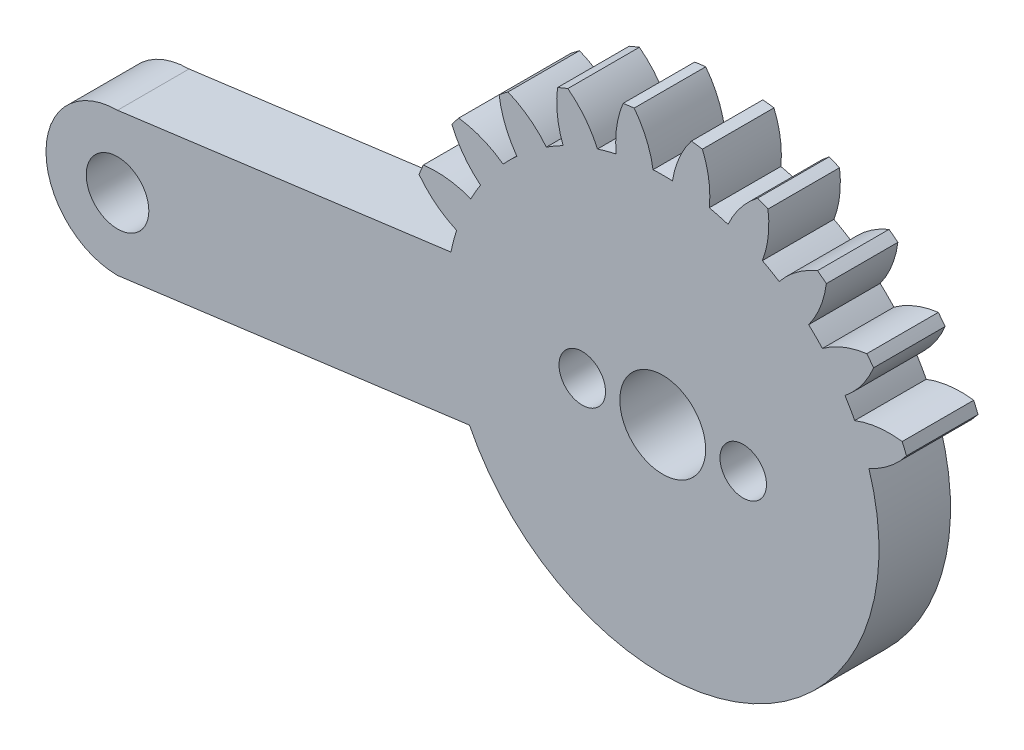
SolidWorks part; units mm, degrees
ref_plane "Front Plane" through (0, 0, 0) normal (0, 0, 1) x (1, 0, 0)
ref_plane "Top Plane" through (0, 0, 0) normal (0, 1, 0) x (1, 0, 0)
ref_plane "Right Plane" through (0, 0, 0) normal (1, 0, 0) x (0, 0, -1)
sketch "Sketch1" plane through (0, 0, 0) normal (0, 0, 1) x (1, 0, 0)
  line L0 (20.64, 4) -> (2.08, 4)
  line L1 (20.64, -4) -> (2.08, -4)
  circle A0 centre (-10.11, 0) radius 1.5
  circle A1 centre (20.64, 0) radius 1.5
  arc A2 (20.64, -4) -> (20.64, 4) centre (20.64, 0) ccw
  arc A3 (2.08, 4) -> (3.5201, 5.3071) centre (-0.7699, 8.5867) ccw
  arc A4 (3.5201, 5.3071) -> (3.2812, 5.8838) centre (-10.108, 0) ccw
  arc A5 (3.2812, 5.8838) -> (0.6255, 5.5703) centre (2.5667, 0.5313) ccw
  arc A6 (0.6255, 5.5703) -> (0.0827, 6.5103) centre (-10.108, 0) ccw
  arc A7 (0.0827, 6.5103) -> (1.6822, 8.6535) centre (-3.3105, 10.711) ccw
  arc A8 (1.6822, 8.6535) -> (1.3022, 9.1487) centre (-10.108, 0) ccw
  arc A9 (1.3022, 9.1487) -> (-1.182, 8.1585) centre (1.9973, 3.7936) ccw
  arc A10 (-1.182, 8.1585) -> (-1.9495, 8.926) centre (-10.108, 0) ccw
  arc A11 (-1.9495, 8.926) -> (-0.9593, 11.4102) centre (-6.3143, 12.1053) ccw
  arc A12 (-0.9593, 11.4102) -> (-1.4545, 11.7901) centre (-10.108, 0) ccw
  arc A13 (-1.4545, 11.7901) -> (-3.5977, 10.1907) centre (0.603, 6.7975) ccw
  arc A14 (-3.5977, 10.1907) -> (-4.5377, 10.7334) centre (-10.108, 0) ccw
  arc A15 (-4.5377, 10.7334) -> (-4.2242, 13.3892) centre (-9.5767, 12.6747) ccw
  arc A16 (-4.2242, 13.3892) -> (-4.8008, 13.6281) centre (-10.108, 0) ccw
  arc A17 (-4.8008, 13.6281) -> (-6.4571, 11.5285) centre (-1.5213, 9.3381) ccw
  arc A18 (-6.4571, 11.5285) -> (-7.5055, 11.8094) centre (-10.108, 0) ccw
  arc A19 (-7.5055, 11.8094) -> (-7.8901, 14.4558) centre (-12.8753, 12.3803) ccw
  arc A20 (-7.8901, 14.4558) -> (-8.5089, 14.5373) centre (-10.108, 0) ccw
  arc A21 (-8.5089, 14.5373) -> (-9.5653, 12.0806) centre (-4.2307, 11.2423) ccw
  arc A22 (-9.5653, 12.0806) -> (-10.6507, 12.0806) centre (-10.108, 0) ccw
  arc A23 (-10.6507, 12.0806) -> (-11.7071, 14.5373) centre (-15.9852, 11.2423) ccw
  arc A24 (-11.7071, 14.5373) -> (-12.3259, 14.4558) centre (-10.108, 0) ccw
  arc A25 (-12.3259, 14.4558) -> (-12.7104, 11.8094) centre (-7.3407, 12.3803) ccw
  arc A26 (-12.7104, 11.8094) -> (-13.7589, 11.5285) centre (-10.108, 0) ccw
  arc A27 (-13.7589, 11.5285) -> (-15.4151, 13.6281) centre (-18.6947, 9.3381) ccw
  arc A28 (-15.4151, 13.6281) -> (-15.9918, 13.3892) centre (-10.108, 0) ccw
  arc A29 (-15.9918, 13.3892) -> (-15.6783, 10.7334) centre (-10.6393, 12.6747) ccw
  arc A30 (-15.6783, 10.7334) -> (-16.6183, 10.1907) centre (-10.108, 0) ccw
  arc A31 (-16.6183, 10.1907) -> (-18.7615, 11.7901) centre (-20.819, 6.7975) ccw
  arc A32 (-18.7615, 11.7901) -> (-19.2567, 11.4102) centre (-10.108, 0) ccw
  arc A33 (-19.2567, 11.4102) -> (-18.2665, 8.926) centre (-13.9016, 12.1053) ccw
  arc A34 (-18.2665, 8.926) -> (-19.034, 8.1585) centre (-10.108, 0) ccw
  arc A35 (-19.034, 8.1585) -> (-21.5181, 9.1487) centre (-22.2133, 3.7936) ccw
  arc A36 (-21.5181, 9.1487) -> (-21.8981, 8.6535) centre (-10.108, 0) ccw
  arc A37 (-21.8981, 8.6535) -> (-20.2987, 6.5103) centre (-16.9054, 10.711) ccw
  arc A38 (-20.2987, 6.5103) -> (-20.8414, 5.5703) centre (-10.108, 0) ccw
  arc A39 (-20.8414, 5.5703) -> (-23.4972, 5.8838) centre (-22.7827, 0.5313) ccw
  arc A40 (-23.4972, 5.8838) -> (-23.7361, 5.3071) centre (-10.108, 0) ccw
  arc A41 (-23.7361, 5.3071) -> (-21.6364, 3.6509) centre (-19.446, 8.5867) ccw
  arc A42 (-21.6364, 3.6509) -> (-21.9174, 2.6025) centre (-10.108, 0) ccw
  arc A43 (-21.9174, 2.6025) -> (-24.5638, 2.2179) centre (-22.4883, -2.7673) ccw
  arc A44 (-24.5638, 2.2179) -> (-24.6453, 1.5991) centre (-10.108, 0) ccw
  arc A45 (-24.6453, 1.5991) -> (-22.1885, 0.5427) centre (-21.3503, 5.8773) ccw
  arc A46 (-22.1885, 0.5427) -> (-22.1885, -0.5427) centre (-10.108, 0) ccw
  arc A47 (-22.1885, -0.5427) -> (-24.6453, -1.5991) centre (-21.3503, -5.8773) ccw
  arc A48 (-24.6453, -1.5991) -> (-24.5638, -2.2179) centre (-10.108, 0) ccw
  arc A49 (-24.5638, -2.2179) -> (-21.9174, -2.6025) centre (-22.4883, 2.7673) ccw
  arc A50 (-21.9174, -2.6025) -> (-21.6364, -3.6509) centre (-10.108, 0) ccw
  arc A51 (-21.6364, -3.6509) -> (-23.7361, -5.3071) centre (-19.446, -8.5867) ccw
  arc A52 (-23.7361, -5.3071) -> (-23.4972, -5.8838) centre (-10.108, 0) ccw
  arc A53 (-23.4972, -5.8838) -> (-20.8414, -5.5703) centre (-22.7827, -0.5313) ccw
  arc A54 (-20.8414, -5.5703) -> (-20.2987, -6.5103) centre (-10.108, 0) ccw
  arc A55 (-20.2987, -6.5103) -> (-21.8981, -8.6535) centre (-16.9054, -10.711) ccw
  arc A56 (-21.8981, -8.6535) -> (-21.5181, -9.1487) centre (-10.108, 0) ccw
  arc A57 (-21.5181, -9.1487) -> (-19.034, -8.1585) centre (-22.2133, -3.7936) ccw
  arc A58 (-19.034, -8.1585) -> (-18.2665, -8.926) centre (-10.108, 0) ccw
  arc A59 (-18.2665, -8.926) -> (-19.2567, -11.4102) centre (-13.9016, -12.1053) ccw
  arc A60 (-19.2567, -11.4102) -> (-18.7615, -11.7901) centre (-10.108, 0) ccw
  arc A61 (-18.7615, -11.7901) -> (-16.6183, -10.1907) centre (-20.819, -6.7975) ccw
  arc A62 (-16.6183, -10.1907) -> (-15.6783, -10.7334) centre (-10.108, 0) ccw
  arc A63 (-15.6783, -10.7334) -> (-15.9918, -13.3892) centre (-10.6393, -12.6747) ccw
  arc A64 (-15.9918, -13.3892) -> (-15.4151, -13.6281) centre (-10.108, 0) ccw
  arc A65 (-15.4151, -13.6281) -> (-13.7589, -11.5285) centre (-18.6947, -9.3381) ccw
  arc A66 (-13.7589, -11.5285) -> (-12.7104, -11.8094) centre (-10.108, 0) ccw
  arc A67 (-12.7104, -11.8094) -> (-12.3259, -14.4558) centre (-7.3407, -12.3803) ccw
  arc A68 (-12.3259, -14.4558) -> (-11.7071, -14.5373) centre (-10.108, 0) ccw
  arc A69 (-11.7071, -14.5373) -> (-10.6507, -12.0806) centre (-15.9852, -11.2423) ccw
  arc A70 (-10.6507, -12.0806) -> (-9.5653, -12.0806) centre (-10.108, 0) ccw
  arc A71 (-9.5653, -12.0806) -> (-8.5089, -14.5373) centre (-4.2307, -11.2423) ccw
  arc A72 (-8.5089, -14.5373) -> (-7.8901, -14.4558) centre (-10.108, 0) ccw
  arc A73 (-7.8901, -14.4558) -> (-7.5055, -11.8094) centre (-12.8753, -12.3803) ccw
  arc A74 (-7.5055, -11.8094) -> (-6.4571, -11.5285) centre (-10.108, 0) ccw
  arc A75 (-6.4571, -11.5285) -> (-4.8008, -13.6281) centre (-1.5213, -9.3381) ccw
  arc A76 (-4.8008, -13.6281) -> (-4.2242, -13.3892) centre (-10.108, 0) ccw
  arc A77 (-4.2242, -13.3892) -> (-4.5377, -10.7334) centre (-9.5767, -12.6747) ccw
  arc A78 (-4.5377, -10.7334) -> (-3.5977, -10.1907) centre (-10.108, 0) ccw
  arc A79 (-3.5977, -10.1907) -> (-1.4545, -11.7901) centre (0.603, -6.7975) ccw
  arc A80 (-1.4545, -11.7901) -> (-0.9593, -11.4102) centre (-10.108, 0) ccw
  arc A81 (-0.9593, -11.4102) -> (-1.9495, -8.926) centre (-6.3143, -12.1053) ccw
  arc A82 (-1.9495, -8.926) -> (-1.182, -8.1585) centre (-10.108, 0) ccw
  arc A83 (-1.182, -8.1585) -> (1.3022, -9.1487) centre (1.9973, -3.7936) ccw
  arc A84 (1.3022, -9.1487) -> (1.6822, -8.6535) centre (-10.108, 0) ccw
  arc A85 (1.6822, -8.6535) -> (0.0827, -6.5103) centre (-3.3105, -10.711) ccw
  arc A86 (0.0827, -6.5103) -> (0.6255, -5.5703) centre (-10.108, 0) ccw
  arc A87 (0.6255, -5.5703) -> (3.2812, -5.8838) centre (2.5667, -0.5313) ccw
  arc A88 (3.2812, -5.8838) -> (3.5201, -5.3071) centre (-10.108, 0) ccw
  arc A89 (3.5201, -5.3071) -> (2.08, -4) centre (-0.7699, -8.5867) ccw
  dimension "D1" = 3
  dimension "D2" = 10.11
  dimension "D4" = 8
  dimension "D3" = 20.64
  dimension "D5" = 18.56
extrude "Boss-Extrude1" add sketch "Sketch1" along normal blind 4
sketch "Sketch2" plane through (0, 0, 4) normal (0, 0, 1) x (1, 0, 0)
  line L0 (-10.11, 0) -> (-41.9779, 0) construction
  line L1 (-10.11, 0) -> (-40.5969, -4.0137)
  line L2 (-10.11, 4) -> (-40.5969, -0.0137)
  line L3 (-10.11, -4) -> (-40.5969, -8.0137)
  line L4 (-10.11, 0) -> (-8.199, 14.4999) construction
  line L5 (-10.11, 0) -> (-4.5112, 13.5117) construction
  circle A0 centre (-10.11, 0) radius 4
  circle A1 centre (-10.11, 0) radius 1.5 construction
  circle A2 centre (-10.11, 0) radius 1.5
  circle A3 centre (-40.5969, -4.0137) radius 4
  circle A4 centre (-40.5969, -4.0137) radius 1.75
  arc A5 (-7.8901, 14.4558) -> (-8.5089, 14.5373) centre (-10.108, 0) ccw construction
  arc A6 (-4.2242, 13.3892) -> (-4.8008, 13.6281) centre (-10.108, 0) ccw construction
  dimension "D1" = 8
  dimension "D2" = 7.5
  dimension "D4" = 3.5
  dimension "D3" = 30.75
extrude "Boss-Extrude2" add sketch "Sketch2" against normal blind 4
sketch "Sketch3" plane through (0, 0, 4) normal (0, 0, 1) x (1, 0, 0)
  line L4 (-24.5822, 2.0947) -> (-40.5969, -0.0137)
  line L5 (-40.5969, -8.0137) -> (-23.5471, -5.769)
  line L6 (2.08, -4) -> (20.64, -4)
  line L7 (20.64, 4) -> (2.08, 4)
  line L8 (-21.9518, 2.441) -> (-40.5969, -0.0137)
  line L9 (-40.5969, -8.0137) -> (-20.9167, -5.4227)
  line L10 (2.08, -4) -> (20.64, -4)
  line L11 (20.64, 4) -> (2.08, 4)
  arc A82 (-24.5638, 2.2179) -> (-24.5822, 2.0947) centre (-10.108, 0) ccw
  arc A83 (-40.5969, -0.0137) -> (-40.5969, -8.0137) centre (-40.5969, -4.0137) ccw
  arc A84 (-23.5471, -5.769) -> (-23.4972, -5.8838) centre (-10.108, 0) ccw
  arc A85 (-23.4972, -5.8838) -> (-20.8414, -5.5703) centre (-22.7827, -0.5313) ccw
  arc A86 (-20.8414, -5.5703) -> (-20.2987, -6.5103) centre (-10.108, 0) ccw
  arc A87 (-20.2987, -6.5103) -> (-21.8981, -8.6535) centre (-16.9054, -10.711) ccw
  arc A88 (-21.8981, -8.6535) -> (-21.5181, -9.1487) centre (-10.108, 0) ccw
  arc A89 (-21.5181, -9.1487) -> (-19.034, -8.1585) centre (-22.2133, -3.7936) ccw
  arc A90 (-19.034, -8.1585) -> (-18.2665, -8.926) centre (-10.108, 0) ccw
  arc A91 (-18.2665, -8.926) -> (-19.2567, -11.4102) centre (-13.9016, -12.1053) ccw
  arc A92 (-19.2567, -11.4102) -> (-18.7615, -11.7901) centre (-10.108, 0) ccw
  arc A93 (-18.7615, -11.7901) -> (-16.6183, -10.1907) centre (-20.819, -6.7975) ccw
  arc A94 (-16.6183, -10.1907) -> (-15.6783, -10.7334) centre (-10.108, 0) ccw
  arc A95 (-15.6783, -10.7334) -> (-15.9918, -13.3892) centre (-10.6393, -12.6747) ccw
  arc A96 (-15.9918, -13.3892) -> (-15.4151, -13.6281) centre (-10.108, 0) ccw
  arc A97 (-15.4151, -13.6281) -> (-13.7589, -11.5285) centre (-18.6947, -9.3381) ccw
  arc A98 (-13.7589, -11.5285) -> (-12.7104, -11.8094) centre (-10.108, 0) ccw
  arc A99 (-12.7104, -11.8094) -> (-12.3259, -14.4558) centre (-7.3407, -12.3803) ccw
  arc A100 (-12.3259, -14.4558) -> (-11.7071, -14.5373) centre (-10.108, 0) ccw
  arc A101 (-11.7071, -14.5373) -> (-10.6507, -12.0806) centre (-15.9852, -11.2423) ccw
  arc A102 (-10.6507, -12.0806) -> (-9.5653, -12.0806) centre (-10.108, 0) ccw
  arc A103 (-9.5653, -12.0806) -> (-8.5089, -14.5373) centre (-4.2307, -11.2423) ccw
  arc A104 (-8.5089, -14.5373) -> (-7.8901, -14.4558) centre (-10.108, 0) ccw
  arc A105 (-7.8901, -14.4558) -> (-7.5055, -11.8094) centre (-12.8753, -12.3803) ccw
  arc A106 (-7.5055, -11.8094) -> (-6.4571, -11.5285) centre (-10.108, 0) ccw
  arc A107 (-6.4571, -11.5285) -> (-4.8008, -13.6281) centre (-1.5213, -9.3381) ccw
  arc A108 (-4.8008, -13.6281) -> (-4.2242, -13.3892) centre (-10.108, 0) ccw
  arc A109 (-4.2242, -13.3892) -> (-4.5377, -10.7334) centre (-9.5767, -12.6747) ccw
  arc A110 (-4.5377, -10.7334) -> (-3.5977, -10.1907) centre (-10.108, 0) ccw
  arc A111 (-3.5977, -10.1907) -> (-1.4545, -11.7901) centre (0.603, -6.7975) ccw
  arc A112 (-1.4545, -11.7901) -> (-0.9593, -11.4102) centre (-10.108, 0) ccw
  arc A113 (-0.9593, -11.4102) -> (-1.9495, -8.926) centre (-6.3143, -12.1053) ccw
  arc A114 (-1.9495, -8.926) -> (-1.182, -8.1585) centre (-10.108, 0) ccw
  arc A115 (-1.182, -8.1585) -> (1.3022, -9.1487) centre (1.9973, -3.7936) ccw
  arc A116 (1.3022, -9.1487) -> (1.6822, -8.6535) centre (-10.108, 0) ccw
  arc A117 (1.6822, -8.6535) -> (0.0827, -6.5103) centre (-3.3105, -10.711) ccw
  arc A118 (0.0827, -6.5103) -> (0.6255, -5.5703) centre (-10.108, 0) ccw
  arc A119 (0.6255, -5.5703) -> (3.2812, -5.8838) centre (2.5667, -0.5313) ccw
  arc A120 (3.2812, -5.8838) -> (3.5201, -5.3071) centre (-10.108, 0) ccw
  arc A121 (3.5201, -5.3071) -> (2.08, -4) centre (-0.7699, -8.5867) ccw
  arc A122 (20.64, -4) -> (20.64, 4) centre (20.64, 0) ccw
  arc A123 (2.08, 4) -> (3.5201, 5.3071) centre (-0.7699, 8.5867) ccw
  arc A124 (3.5201, 5.3071) -> (3.2812, 5.8838) centre (-10.108, 0) ccw
  arc A125 (3.2812, 5.8838) -> (0.6255, 5.5703) centre (2.5667, 0.5313) ccw
  arc A126 (0.6255, 5.5703) -> (0.0827, 6.5103) centre (-10.108, 0) ccw
  arc A127 (0.0827, 6.5103) -> (1.6822, 8.6535) centre (-3.3105, 10.711) ccw
  arc A128 (1.6822, 8.6535) -> (1.3022, 9.1487) centre (-10.108, 0) ccw
  arc A129 (1.3022, 9.1487) -> (-1.182, 8.1585) centre (1.9973, 3.7936) ccw
  arc A130 (-1.182, 8.1585) -> (-1.9495, 8.926) centre (-10.108, 0) ccw
  arc A131 (-1.9495, 8.926) -> (-0.9593, 11.4102) centre (-6.3143, 12.1053) ccw
  arc A132 (-0.9593, 11.4102) -> (-1.4545, 11.7901) centre (-10.108, 0) ccw
  arc A133 (-1.4545, 11.7901) -> (-3.5977, 10.1907) centre (0.603, 6.7975) ccw
  arc A134 (-3.5977, 10.1907) -> (-4.5377, 10.7334) centre (-10.108, 0) ccw
  arc A135 (-4.5377, 10.7334) -> (-4.2242, 13.3892) centre (-9.5767, 12.6747) ccw
  arc A136 (-4.2242, 13.3892) -> (-4.8008, 13.6281) centre (-10.108, 0) ccw
  arc A137 (-4.8008, 13.6281) -> (-6.4571, 11.5285) centre (-1.5213, 9.3381) ccw
  arc A138 (-6.4571, 11.5285) -> (-7.5055, 11.8094) centre (-10.108, 0) ccw
  arc A139 (-7.5055, 11.8094) -> (-7.8901, 14.4558) centre (-12.8753, 12.3803) ccw
  arc A140 (-7.8901, 14.4558) -> (-8.5089, 14.5373) centre (-10.108, 0) ccw
  arc A141 (-8.5089, 14.5373) -> (-9.5653, 12.0806) centre (-4.2307, 11.2423) ccw
  arc A142 (-9.5653, 12.0806) -> (-10.6507, 12.0806) centre (-10.108, 0) ccw
  arc A143 (-10.6507, 12.0806) -> (-11.7071, 14.5373) centre (-15.9852, 11.2423) ccw
  arc A144 (-11.7071, 14.5373) -> (-12.3259, 14.4558) centre (-10.108, 0) ccw
  arc A145 (-12.3259, 14.4558) -> (-12.7104, 11.8094) centre (-7.3407, 12.3803) ccw
  arc A146 (-12.7104, 11.8094) -> (-13.7589, 11.5285) centre (-10.108, 0) ccw
  arc A147 (-13.7589, 11.5285) -> (-15.4151, 13.6281) centre (-18.6947, 9.3381) ccw
  arc A148 (-15.4151, 13.6281) -> (-15.9918, 13.3892) centre (-10.108, 0) ccw
  arc A149 (-15.9918, 13.3892) -> (-15.6783, 10.7334) centre (-10.6393, 12.6747) ccw
  arc A150 (-15.6783, 10.7334) -> (-16.6183, 10.1907) centre (-10.108, 0) ccw
  arc A151 (-16.6183, 10.1907) -> (-18.7615, 11.7901) centre (-20.819, 6.7975) ccw
  arc A152 (-18.7615, 11.7901) -> (-19.2567, 11.4102) centre (-10.108, 0) ccw
  arc A153 (-19.2567, 11.4102) -> (-18.2665, 8.926) centre (-13.9016, 12.1053) ccw
  arc A154 (-18.2665, 8.926) -> (-19.034, 8.1585) centre (-10.108, 0) ccw
  arc A155 (-19.034, 8.1585) -> (-21.5181, 9.1487) centre (-22.2133, 3.7936) ccw
  arc A156 (-21.5181, 9.1487) -> (-21.8981, 8.6535) centre (-10.108, 0) ccw
  arc A157 (-21.8981, 8.6535) -> (-20.2987, 6.5103) centre (-16.9054, 10.711) ccw
  arc A158 (-20.2987, 6.5103) -> (-20.8414, 5.5703) centre (-10.108, 0) ccw
  arc A159 (-20.8414, 5.5703) -> (-23.4972, 5.8838) centre (-22.7827, 0.5313) ccw
  arc A160 (-23.4972, 5.8838) -> (-23.7361, 5.3071) centre (-10.108, 0) ccw
  arc A161 (-23.7361, 5.3071) -> (-21.6364, 3.6509) centre (-19.446, 8.5867) ccw
  arc A162 (-21.6364, 3.6509) -> (-21.9174, 2.6025) centre (-10.108, 0) ccw
  arc A163 (-21.9174, 2.6025) -> (-24.5638, 2.2179) centre (-22.4883, -2.7673) ccw
  arc A164 (-24.5638, 2.2179) -> (-24.5822, 2.0947) centre (-10.108, 0) ccw
  arc A165 (-40.5969, -0.0137) -> (-40.5969, -8.0137) centre (-40.5969, -4.0137) ccw
  arc A166 (-23.5471, -5.769) -> (-23.4972, -5.8838) centre (-10.108, 0) ccw
  arc A167 (-23.4972, -5.8838) -> (-20.8414, -5.5703) centre (-22.7827, -0.5313) ccw
  arc A168 (-21.9174, 2.6025) -> (-20.2987, -6.5103) centre (-10.108, 0) ccw
  arc A169 (-20.2987, -6.5103) -> (-21.8981, -8.6535) centre (-16.9054, -10.711) ccw
  arc A170 (-21.8981, -8.6535) -> (-21.5181, -9.1487) centre (-10.108, 0) ccw
  arc A171 (-21.5181, -9.1487) -> (-19.034, -8.1585) centre (-22.2133, -3.7936) ccw
  arc A172 (-20.8414, -5.5703) -> (-16.6183, -10.1907) centre (-10.108, 0) ccw
  arc A173 (-18.2665, -8.926) -> (-19.2567, -11.4102) centre (-13.9016, -12.1053) ccw
  arc A174 (-19.2567, -11.4102) -> (-18.7615, -11.7901) centre (-10.108, 0) ccw
  arc A175 (-18.7615, -11.7901) -> (-16.6183, -10.1907) centre (-20.819, -6.7975) ccw
  arc A176 (-18.2665, -8.926) -> (-15.6783, -10.7334) centre (-10.108, 0) ccw
  arc A177 (-15.6783, -10.7334) -> (-15.9918, -13.3892) centre (-10.6393, -12.6747) ccw
  arc A178 (-15.9918, -13.3892) -> (-15.4151, -13.6281) centre (-10.108, 0) ccw
  arc A179 (-15.4151, -13.6281) -> (-13.7589, -11.5285) centre (-18.6947, -9.3381) ccw
  arc A180 (-15.6783, -10.7334) -> (-12.7104, -11.8094) centre (-10.108, 0) ccw
  arc A181 (-12.7104, -11.8094) -> (-12.3259, -14.4558) centre (-7.3407, -12.3803) ccw
  arc A182 (-12.3259, -14.4558) -> (-11.7071, -14.5373) centre (-10.108, 0) ccw
  arc A183 (-11.7071, -14.5373) -> (-10.6507, -12.0806) centre (-15.9852, -11.2423) ccw
  arc A184 (-12.7104, -11.8094) -> (-9.5653, -12.0806) centre (-10.108, 0) ccw
  arc A185 (-9.5653, -12.0806) -> (-8.5089, -14.5373) centre (-4.2307, -11.2423) ccw
  arc A186 (-8.5089, -14.5373) -> (-7.8901, -14.4558) centre (-10.108, 0) ccw
  arc A187 (-7.8901, -14.4558) -> (-7.5055, -11.8094) centre (-12.8753, -12.3803) ccw
  arc A188 (-9.5653, -12.0806) -> (-6.4571, -11.5285) centre (-10.108, 0) ccw
  arc A189 (-6.4571, -11.5285) -> (-4.8008, -13.6281) centre (-1.5213, -9.3381) ccw
  arc A190 (-4.8008, -13.6281) -> (-4.2242, -13.3892) centre (-10.108, 0) ccw
  arc A191 (-4.2242, -13.3892) -> (-4.5377, -10.7334) centre (-9.5767, -12.6747) ccw
  arc A192 (-6.4571, -11.5285) -> (-3.5977, -10.1907) centre (-10.108, 0) ccw
  arc A193 (-3.5977, -10.1907) -> (-1.4545, -11.7901) centre (0.603, -6.7975) ccw
  arc A194 (-1.4545, -11.7901) -> (-0.9593, -11.4102) centre (-10.108, 0) ccw
  arc A195 (-0.9593, -11.4102) -> (-1.9495, -8.926) centre (-6.3143, -12.1053) ccw
  arc A196 (-3.5977, -10.1907) -> (-1.182, -8.1585) centre (-10.108, 0) ccw
  arc A197 (-1.182, -8.1585) -> (1.3022, -9.1487) centre (1.9973, -3.7936) ccw
  arc A198 (1.3022, -9.1487) -> (1.6822, -8.6535) centre (-10.108, 0) ccw
  arc A199 (1.6822, -8.6535) -> (0.0827, -6.5103) centre (-3.3105, -10.711) ccw
  arc A200 (-1.182, -8.1585) -> (0.6255, -5.5703) centre (-10.108, 0) ccw
  arc A201 (0.6255, -5.5703) -> (3.2812, -5.8838) centre (2.5667, -0.5313) ccw
  arc A202 (3.2812, -5.8838) -> (3.5201, -5.3071) centre (-10.108, 0) ccw
  arc A203 (3.5201, -5.3071) -> (2.08, -4) centre (-0.7699, -8.5867) ccw
  arc A204 (20.64, -4) -> (20.64, 4) centre (20.64, 0) ccw
  arc A205 (1.4205, 3.6509) -> (3.5201, 5.3071) centre (-0.7699, 8.5867) ccw
  arc A206 (3.5201, 5.3071) -> (3.2812, 5.8838) centre (-10.108, 0) ccw
  arc A207 (3.2812, 5.8838) -> (0.6255, 5.5703) centre (2.5667, 0.5313) ccw
  arc A208 (0.6255, -5.5703) -> (-1.182, 8.1585) centre (-10.108, 0) ccw
  arc A209 (0.0827, 6.5103) -> (1.6822, 8.6535) centre (-3.3105, 10.711) ccw
  arc A210 (1.6822, 8.6535) -> (1.3022, 9.1487) centre (-10.108, 0) ccw
  arc A211 (1.3022, 9.1487) -> (-1.182, 8.1585) centre (1.9973, 3.7936) ccw
  arc A212 (-1.182, 8.1585) -> (-3.5977, 10.1907) centre (-10.108, 0) ccw
  arc A213 (-1.9495, 8.926) -> (-0.9593, 11.4102) centre (-6.3143, 12.1053) ccw
  arc A214 (-0.9593, 11.4102) -> (-1.4545, 11.7901) centre (-10.108, 0) ccw
  arc A215 (-1.4545, 11.7901) -> (-3.5977, 10.1907) centre (0.603, 6.7975) ccw
  arc A216 (-3.5977, 10.1907) -> (-6.4571, 11.5285) centre (-10.108, 0) ccw
  arc A217 (-4.5377, 10.7334) -> (-4.2242, 13.3892) centre (-9.5767, 12.6747) ccw
  arc A218 (-4.2242, 13.3892) -> (-4.8008, 13.6281) centre (-10.108, 0) ccw
  arc A219 (-4.8008, 13.6281) -> (-6.4571, 11.5285) centre (-1.5213, 9.3381) ccw
  arc A220 (-6.4571, 11.5285) -> (-9.5653, 12.0806) centre (-10.108, 0) ccw
  arc A221 (-7.5055, 11.8094) -> (-7.8901, 14.4558) centre (-12.8753, 12.3803) ccw
  arc A222 (-7.8901, 14.4558) -> (-8.5089, 14.5373) centre (-10.108, 0) ccw
  arc A223 (-8.5089, 14.5373) -> (-9.5653, 12.0806) centre (-4.2307, 11.2423) ccw
  arc A224 (-7.5055, 11.8094) -> (-10.6507, 12.0806) centre (-10.108, 0) ccw
  arc A225 (-10.6507, 12.0806) -> (-11.7071, 14.5373) centre (-15.9852, 11.2423) ccw
  arc A226 (-11.7071, 14.5373) -> (-12.3259, 14.4558) centre (-10.108, 0) ccw
  arc A227 (-12.3259, 14.4558) -> (-12.7104, 11.8094) centre (-7.3407, 12.3803) ccw
  arc A228 (-10.6507, 12.0806) -> (-13.7589, 11.5285) centre (-10.108, 0) ccw
  arc A229 (-13.7589, 11.5285) -> (-15.4151, 13.6281) centre (-18.6947, 9.3381) ccw
  arc A230 (-15.4151, 13.6281) -> (-15.9918, 13.3892) centre (-10.108, 0) ccw
  arc A231 (-15.9918, 13.3892) -> (-15.6783, 10.7334) centre (-10.6393, 12.6747) ccw
  arc A232 (-13.7589, 11.5285) -> (-16.6183, 10.1907) centre (-10.108, 0) ccw
  arc A233 (-16.6183, 10.1907) -> (-18.7615, 11.7901) centre (-20.819, 6.7975) ccw
  arc A234 (-18.7615, 11.7901) -> (-19.2567, 11.4102) centre (-10.108, 0) ccw
  arc A235 (-19.2567, 11.4102) -> (-18.2665, 8.926) centre (-13.9016, 12.1053) ccw
  arc A236 (-16.6183, 10.1907) -> (-19.034, 8.1585) centre (-10.108, 0) ccw
  arc A237 (-19.034, 8.1585) -> (-21.5181, 9.1487) centre (-22.2133, 3.7936) ccw
  arc A238 (-21.5181, 9.1487) -> (-21.8981, 8.6535) centre (-10.108, 0) ccw
  arc A239 (-21.8981, 8.6535) -> (-20.2987, 6.5103) centre (-16.9054, 10.711) ccw
  arc A240 (-19.034, 8.1585) -> (-20.8414, 5.5703) centre (-10.108, 0) ccw
  arc A241 (-20.8414, 5.5703) -> (-23.4972, 5.8838) centre (-22.7827, 0.5313) ccw
  arc A242 (-23.4972, 5.8838) -> (-23.7361, 5.3071) centre (-10.108, 0) ccw
  arc A243 (-23.7361, 5.3071) -> (-21.6364, 3.6509) centre (-19.446, 8.5867) ccw
  arc A244 (-20.8414, 5.5703) -> (-20.8414, -5.5703) centre (-10.108, 0) ccw
  arc A245 (-21.9174, 2.6025) -> (-24.5638, 2.2179) centre (-22.4883, -2.7673) ccw
  dimension "D1" = 0
extrude "Cut-Extrude1" cut sketch "Sketch3" against normal through all contours A168 A245 A164 L8 | A168 L9 A166 A167 | A208 A201 A202 A203 L10 A204 L11 A205 | A200 A197 A198 A199 | A196 A193 A194 A195 | A192 A189 A190 A191 | A188 A185 A186 A187 | A184 A181 A182 A183 | A180 A177 A178 A179 | A174 A175 A172 A173 | A172 A169 A170 A171
sketch "Sketch4" plane through (0, 0, 4) normal (0, 0, 1) x (1, 0, 0)
  circle A0 centre (-10.11, 0) radius 2.4
  circle A1 centre (-5.61, 0) radius 1.3
  circle A2 centre (-14.61, 0) radius 1.3
  dimension "D1" = 4.8
  dimension "D2" = 2.6
  dimension "D3" = 9
  dimension "D4" = 4.5
extrude "Cut-Extrude2" cut sketch "Sketch4" against normal through all
